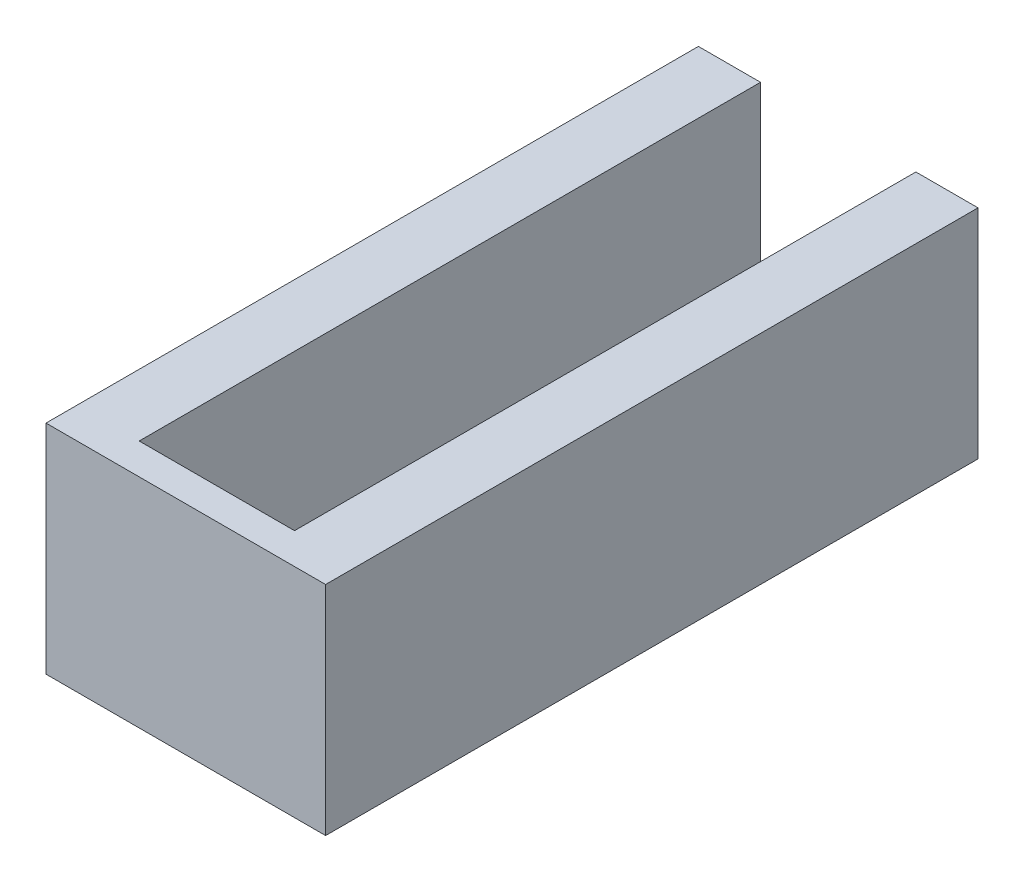
SolidWorks part; units mm, degrees
ref_plane "Front Plane" through (0, 0, 0) normal (0, 0, 1) x (1, 0, 0)
ref_plane "Top Plane" through (0, 0, 0) normal (0, 1, 0) x (1, 0, 0)
ref_plane "Right Plane" through (0, 0, 0) normal (1, 0, 0) x (0, 0, -1)
sketch "Sketch1" plane through (0, 0, 0) normal (0, 0, 1) x (1, 0, 0)
  line L0 (0, 0) -> (0, -7)
  line L1 (0, -7) -> (-9, -7)
  line L2 (-9, -7) -> (-9, 0)
  line L3 (-2, 0) -> (-2, -5)
  line L4 (-2, -5) -> (-7, -5)
  line L5 (-7, -5) -> (-7, 0)
  line L6 (-9, 0) -> (-7, 0)
  line L7 (0, 0) -> (-2, 0)
  dimension "D1" = 2
extrude "Boss-Extrude1" add sketch "Sketch1" along normal blind 20
sketch "Sketch3" plane through (0, 0, 20) normal (0, 0, 1) x (1, 0, 0)
  line L1 (-9, -7) -> (0, -7)
  line L2 (-9, -7) -> (-9, 0)
  line L3 (-9, 0) -> (0, 0)
  line L4 (0, -7) -> (0, 0)
extrude "Boss-Extrude2" add sketch "Sketch3" along normal blind 1
